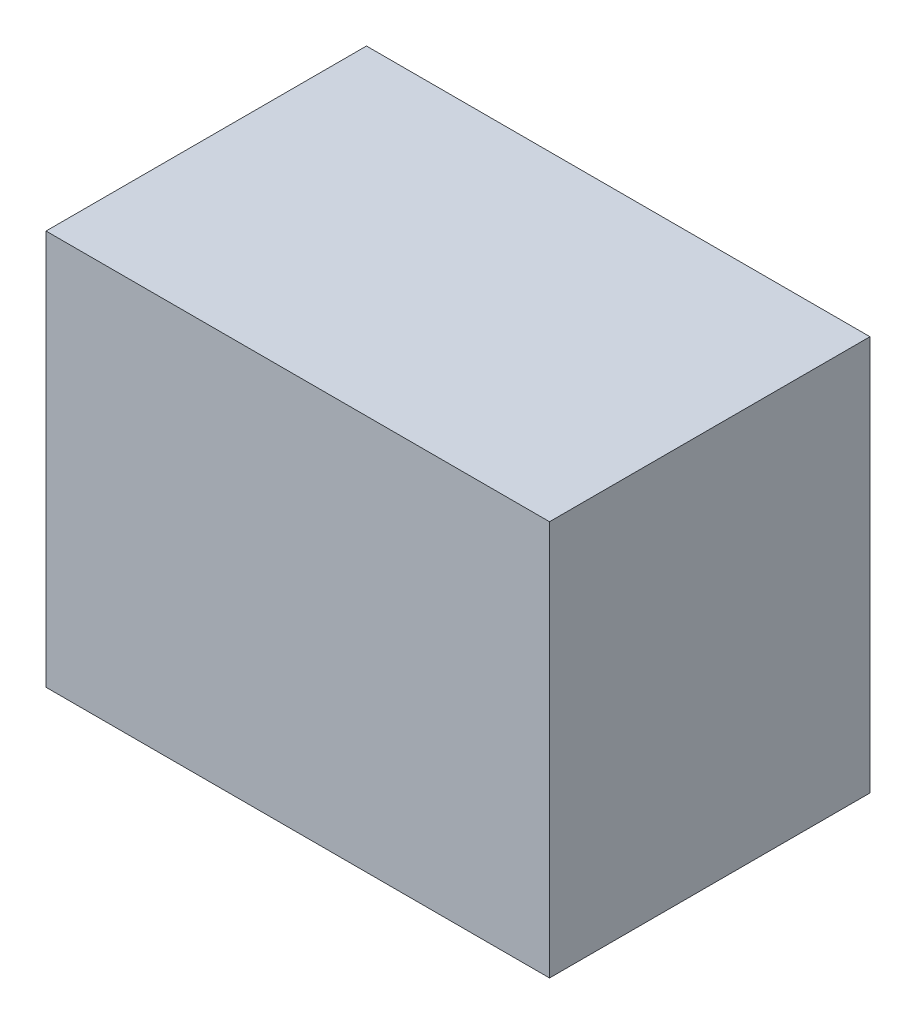
SolidWorks part; units mm, degrees
ref_plane "Front Plane" through (0, 0, 0) normal (0, 0, 1) x (1, 0, 0)
ref_plane "Top Plane" through (0, 0, 0) normal (0, 1, 0) x (1, 0, 0)
ref_plane "Right Plane" through (0, 0, 0) normal (1, 0, 0) x (0, 0, -1)
sketch "Sketch1" plane through (0, 0, 0) normal (0, 1, 0) x (1, 0, 0)
  line L1 (-27.3, -17.375) -> (27.3, -17.375)
  line L2 (-27.3, -17.375) -> (-27.3, 17.375)
  line L3 (-27.3, 17.375) -> (27.3, 17.375)
  line L4 (27.3, -17.375) -> (27.3, 17.375)
  line L5 (-27.3, -17.375) -> (27.3, 17.375) construction
  line L6 (-27.3, 17.375) -> (27.3, -17.375) construction
  point P0 (0, 0)
  dimension "D1" = 54.6
  dimension "D2" = 34.75
extrude "Boss-Extrude1" add sketch "Sketch1" along normal blind 42.85
